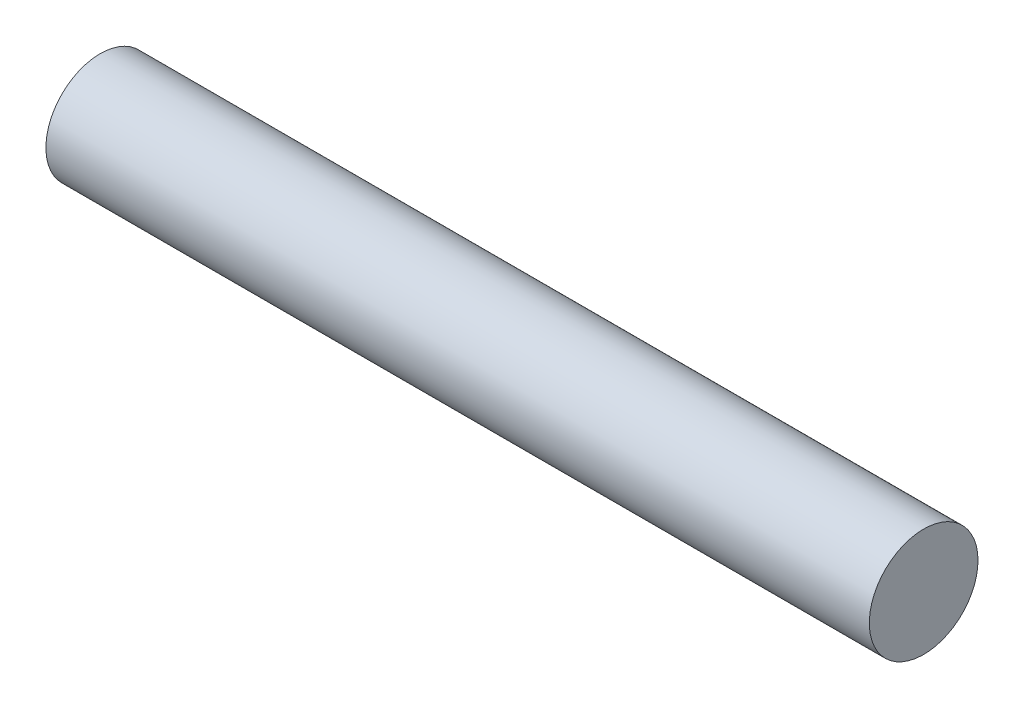
SolidWorks part; units mm, degrees
ref_plane "前视基准面" through (0, 0, 0) normal (0, 0, 1) x (1, 0, 0)
ref_plane "上视基准面" through (0, 0, 0) normal (0, 1, 0) x (1, 0, 0)
ref_plane "右视基准面" through (0, 0, 0) normal (1, 0, 0) x (0, 0, -1)
sketch "草图1" plane through (0, 0, 0) normal (1, 0, 0) x (0, 0, -1)
  circle A0 centre (0, 0) radius 1.65
extrude "凸台-拉伸1" add sketch "草图1" along normal blind 25
